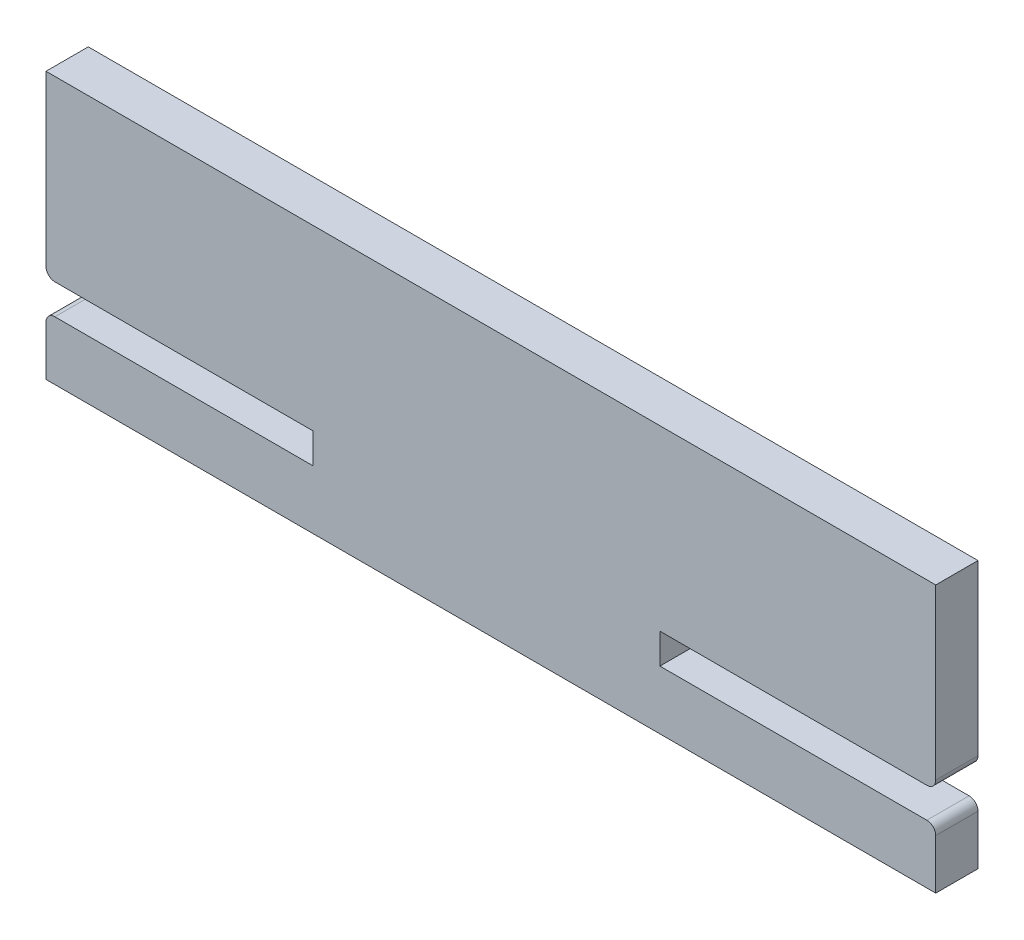
SolidWorks part; units mm, degrees
ref_plane "Front Plane" through (0, 0, 0) normal (0, 0, 1) x (1, 0, 0)
ref_plane "Top Plane" through (0, 0, 0) normal (0, 1, 0) x (1, 0, 0)
ref_plane "Right Plane" through (0, 0, 0) normal (1, 0, 0) x (0, 0, -1)
sketch "Sketch1" plane through (0, 0, 0) normal (0, 0, 1) x (1, 0, 0)
  line L0 (-37.7047, -5) -> (-8.7047, -5)
  line L1 (-38.7047, 15) -> (61.2953, 15)
  line L2 (-38.7047, 15) -> (-38.7047, -4)
  line L3 (-38.7047, -15) -> (61.2953, -15)
  line L4 (61.2953, 15) -> (61.2953, -4)
  line L5 (-8.7047, -5) -> (-8.7047, -8.4)
  line L6 (-8.7047, -8.4) -> (-37.7047, -8.4)
  line L8 (-38.7047, -9.4) -> (-38.7047, -15)
  line L9 (30.2953, -8.4) -> (60.2953, -8.4)
  line L10 (60.2953, -5) -> (30.2953, -5)
  line L11 (30.2953, -5) -> (30.2953, -8.4)
  line L12 (61.2953, -9.4) -> (61.2953, -15)
  arc A0 (60.2953, -8.4) -> (61.2953, -9.4) centre (60.2953, -9.4) cw
  arc A1 (60.2953, -5) -> (61.2953, -4) centre (60.2953, -4) ccw
  arc A2 (-37.7047, -8.4) -> (-38.7047, -9.4) centre (-37.7047, -9.4) ccw
  arc A3 (-37.7047, -5) -> (-38.7047, -4) centre (-37.7047, -4) cw
  point P0 (0, 0)
  point P18 (61.2953, -8.4)
  point P21 (61.2953, -5)
  point P24 (-38.7047, -8.4)
  point P27 (-38.7047, -5)
  dimension "D5" = 1
  dimension "D1" = 30
  dimension "D2" = 30
  dimension "D3" = 3.4
  dimension "D4" = 20
  dimension "D6" = 100
  dimension "D7" = 30
  dimension "D8" = 3.4
extrude "Boss-Extrude1" add sketch "Sketch1" along normal blind 4.75
